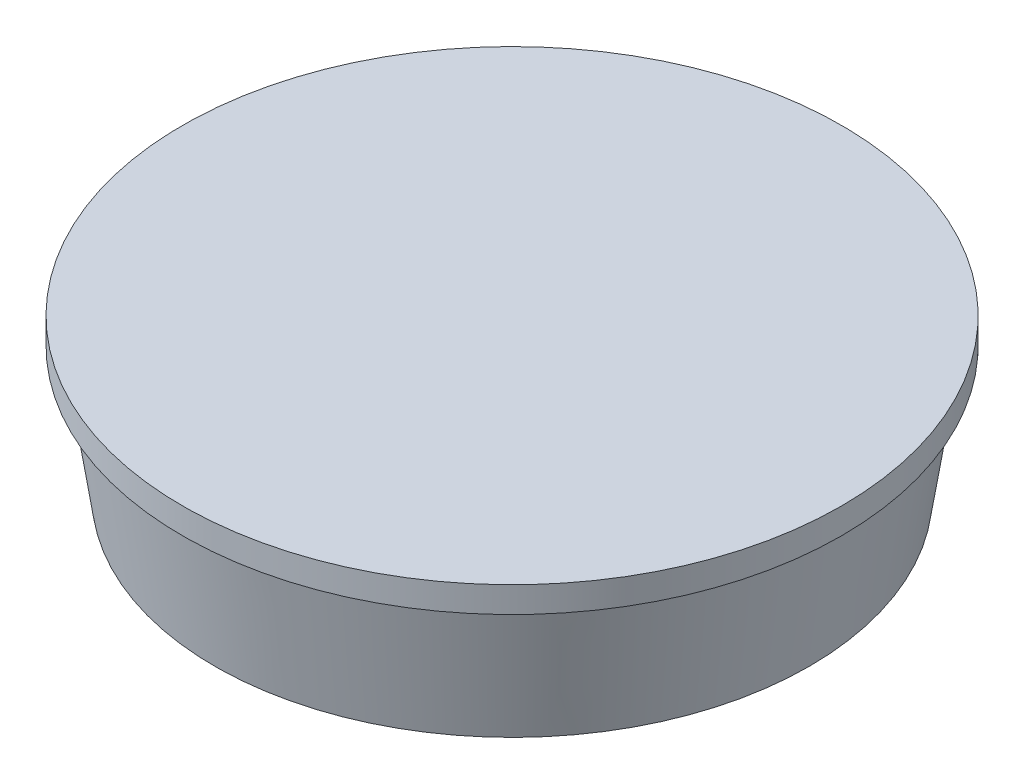
SolidWorks part; units mm, degrees
ref_plane "Front Plane" through (0, 0, 0) normal (0, 0, 1) x (1, 0, 0)
ref_plane "Top Plane" through (0, 0, 0) normal (0, 1, 0) x (1, 0, 0)
ref_plane "Right Plane" through (0, 0, 0) normal (1, 0, 0) x (0, 0, -1)
sketch "Sketch2" plane through (0, 0, 0) normal (0, 0, 1) x (1, 0, 0)
  line L1 (-25.5, 0) -> (-25.5, -2) construction
  line L2 (-25.5, -2) -> (-24.5, -2) construction
  line L3 (-24.5, -2) -> (-23, -12) construction
  line L4 (-23, -12) -> (-22, -12) construction
  line L5 (-22, -12) -> (-22, -2) construction
  line L7 (0, -3.85) -> (0, 3.85) construction
  line L8 (22, -12) -> (22, -2)
  line L9 (23, -12) -> (22, -12)
  line L10 (24.5, -2) -> (23, -12)
  line L11 (25.5, -2) -> (24.5, -2)
  line L12 (25.5, 0) -> (25.5, -2)
  line L13 (0, 0) -> (0, -2) construction
  line L14 (-25.5, 0) -> (0, 0) construction
  line L15 (0, 0) -> (25.5, 0)
  line L16 (-22, -2) -> (0, -2) construction
  line L17 (0, -2) -> (22, -2)
  line L18 (0, -2) -> (0, 0)
  point P17 (0, 0)
  dimension "D1" = 51
  dimension "D2" = 46
  dimension "D3" = 49
  dimension "D4" = 1
  dimension "D5" = 2
  dimension "D6" = 10
revolve "Revolve3" add sketch "Sketch2" angle 360 about L18
fillet "Fillet1" radius 4 1 edges at (22, -2, 0)
